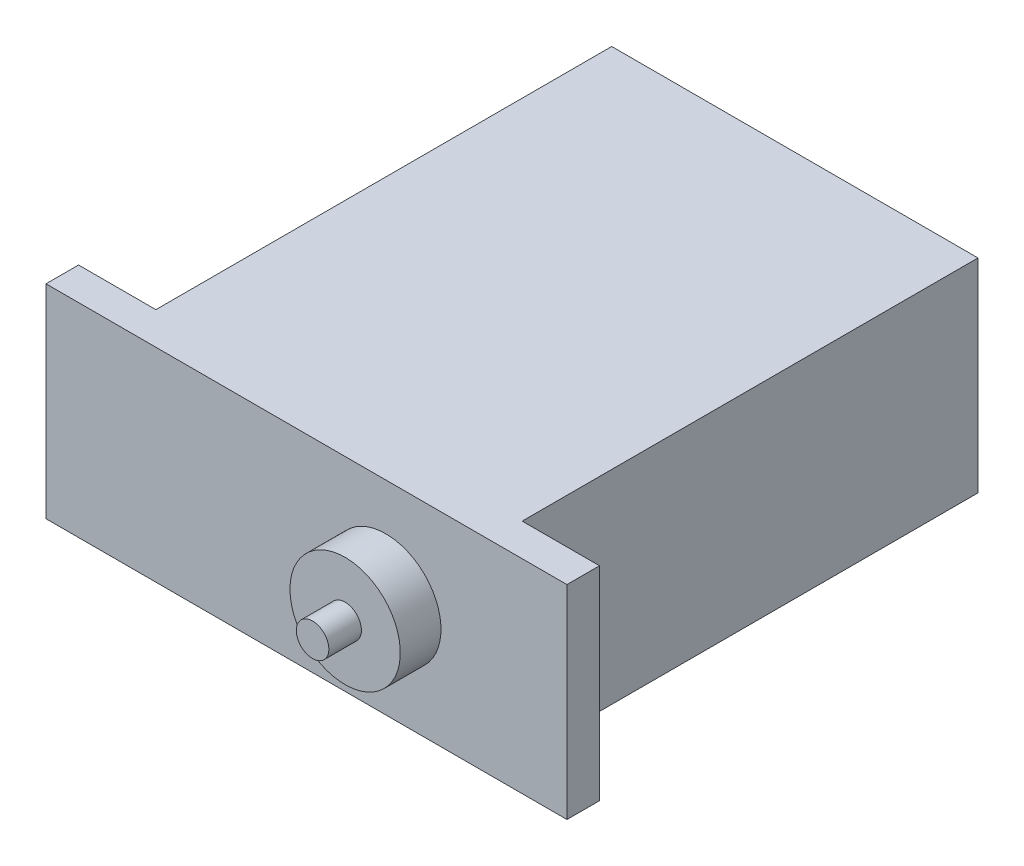
SolidWorks part; units mm, degrees
ref_plane "前视基准面" through (0, 0, 0) normal (0, 0, 1) x (1, 0, 0)
ref_plane "上视基准面" through (0, 0, 0) normal (0, 1, 0) x (1, 0, 0)
ref_plane "右视基准面" through (0, 0, 0) normal (1, 0, 0) x (0, 0, -1)
sketch "草图1" plane through (0, 0, 0) normal (0, 0, 1) x (1, 0, 0)
  line L1 (-11.25, 6.25) -> (11.25, 6.25)
  line L2 (-11.25, 6.25) -> (-11.25, -6.25)
  line L3 (-11.25, -6.25) -> (11.25, -6.25)
  line L4 (11.25, 6.25) -> (11.25, -6.25)
  line L5 (-11.25, 6.25) -> (11.25, -6.25) construction
  line L6 (-11.25, -6.25) -> (11.25, 6.25) construction
  point P0 (0, 0)
  dimension "D1" = 12.5
  dimension "D2" = 22.5
extrude "凸台-拉伸1" add sketch "草图1" along normal blind 28
sketch "草图2" plane through (0, 0, 28) normal (0, 0, 1) x (1, 0, 0)
  line L1 (-16, -6.25) -> (16, -6.25)
  line L2 (-16, -6.25) -> (-16, 6.25)
  line L3 (-16, 6.25) -> (16, 6.25)
  line L4 (16, -6.25) -> (16, 6.25)
  line L5 (-16, -6.25) -> (16, 6.25) construction
  line L6 (-16, 6.25) -> (16, -6.25) construction
  point P0 (0, 0)
  dimension "D1" = 32
  dimension "D2" = 12.5
extrude "凸台-拉伸2" add sketch "草图2" along normal blind 2
sketch "草图3" plane through (0, 0, 30) normal (0, 0, 1) x (1, 0, 0)
  circle A0 centre (4.8743, 0) radius 3.3887
extrude "凸台-拉伸3" add sketch "草图3" along normal offset from surface (2.5 mm away) 32.5 up to face at (0, 0, 0)
sketch "草图4" plane through (0, 0, 32.5) normal (0, 0, 1) x (1, 0, 0)
  circle A0 centre (4.8743, 0) radius 1
  dimension "D1" = 2
extrude "凸台-拉伸4" add sketch "草图4" along normal blind 2
